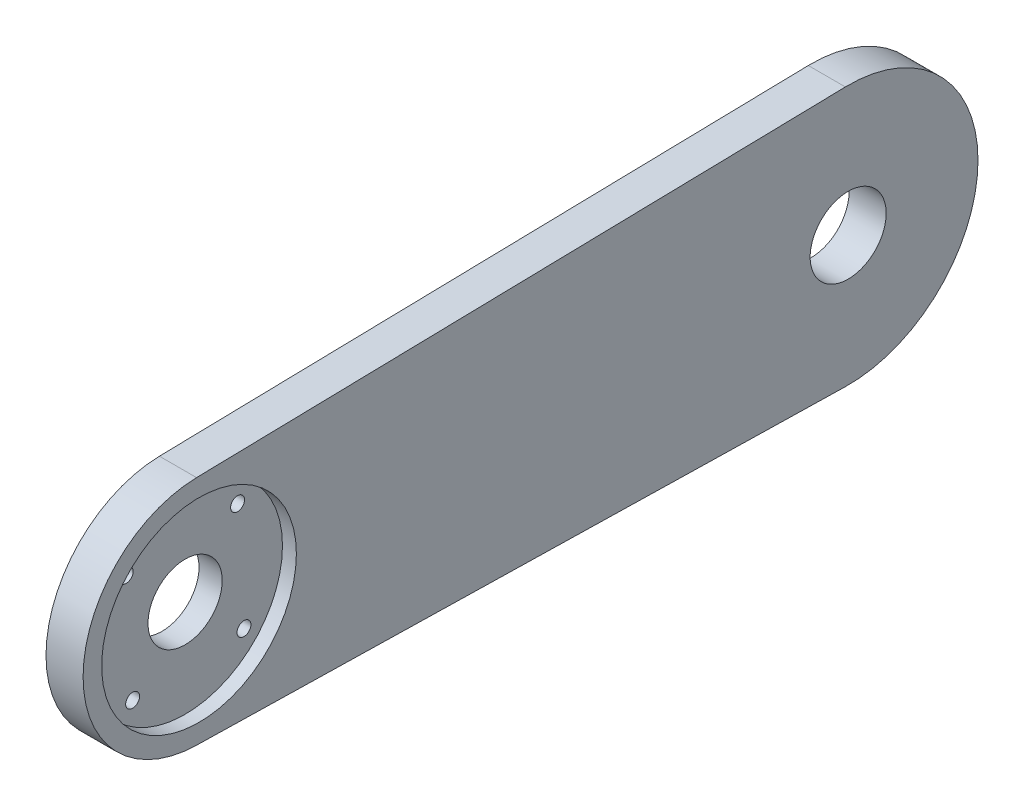
SolidWorks part; units mm, degrees
ref_plane "Alzado" through (0, 0, 0) normal (0, 0, 1) x (1, 0, 0)
ref_plane "Planta" through (0, 0, 0) normal (0, 1, 0) x (1, 0, 0)
ref_plane "Vista lateral" through (0, 0, 0) normal (1, 0, 0) x (0, 0, -1)
sketch "Croquis1" plane through (0, 0, 0) normal (1, 0, 0) x (0, 0, -1)
  line L0 (0, 0) -> (-98.2419, 0) construction
  line L1 (-70.2679, 12.4971) -> (-0.3, 13.9968)
  line L2 (-70.2679, -12.4971) -> (-0.3, -13.9968)
  circle A0 centre (0, 0) radius 4.1
  arc A1 (-0.3, -13.9968) -> (-0.3, 13.9968) centre (0, 0) ccw
  circle A2 centre (-70, 0) radius 4
  arc A3 (-70.2679, 12.4971) -> (-70.2679, -12.4971) centre (-70, 0) ccw
  dimension "D1" = 8.2
  dimension "D2" = 28
  dimension "D3" = 25
  dimension "D4" = 70
  dimension "D5" = 8
extrude "Saliente-Extruir1" add sketch "Croquis1" along normal blind 4
sketch "Croquis2" plane through (4, 0, 0) normal (1, 0, 0) x (0, 0, -1)
  circle A0 centre (-70, 0) radius 10.5
  dimension "D1" = 21
extrude "Cortar-Extruir1" cut sketch "Croquis2" against normal blind 1.5
sketch "Croquis3" plane through (0, 0, 0) normal (-1, 0, 0) x (0, 0, 1)
  circle A0 centre (63.6519, -5.6581) radius 0.75
  circle A1 centre (76.3481, 5.6581) radius 0.75
  circle A2 centre (64.3419, 6.3481) radius 0.75
  circle A3 centre (75.6581, -6.3481) radius 0.75
  dimension "D1" = 1.5
extrude "Cortar-Extruir2" cut sketch "Croquis3" against normal blind 10
